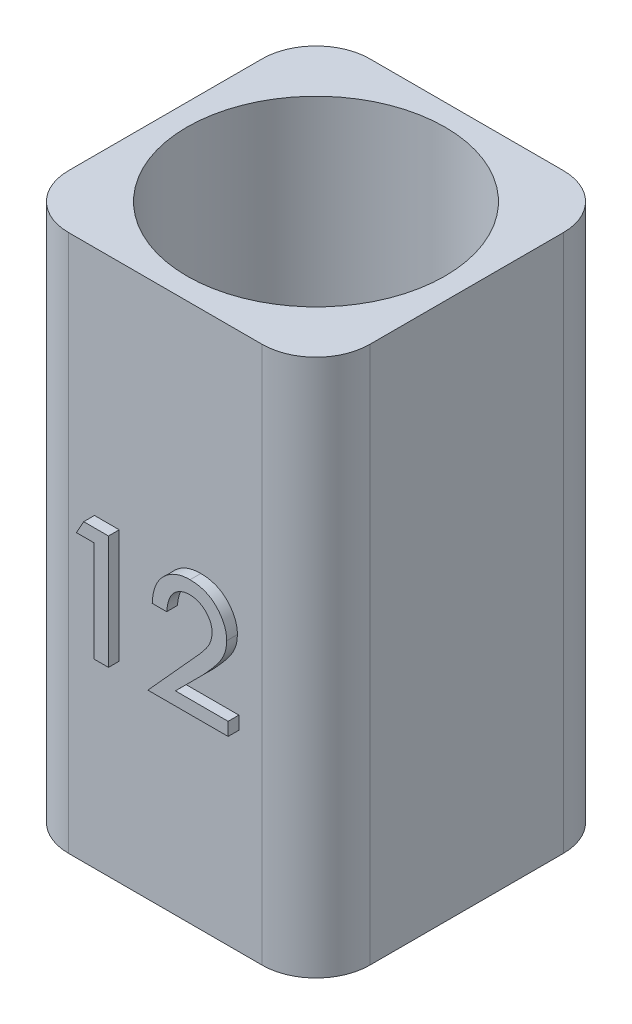
SolidWorks part; units mm, degrees
ref_plane "Ebene vorne" through (0, 0, 0) normal (0, 0, 1) x (1, 0, 0)
ref_plane "Ebene oben" through (0, 0, 0) normal (0, 1, 0) x (1, 0, 0)
ref_plane "Ebene rechts" through (0, 0, 0) normal (1, 0, 0) x (0, 0, -1)
sketch "Sketch1" plane through (0, 0, 0) normal (0, 1, 0) x (1, 0, 0)
  line L1 (7, -7) -> (-7, -7)
  line L2 (7, -7) -> (7, 7)
  line L3 (7, 7) -> (-7, 7)
  line L4 (-7, -7) -> (-7, 7)
  line L5 (7, -7) -> (-7, 7) construction
  line L6 (7, 7) -> (-7, -7) construction
  point P0 (0, 0)
  dimension "D1" = 14
  dimension "D2" = 14
extrude "Boss-Extrude1" add sketch "Sketch1" along normal blind 25
sketch "Sketch2" plane through (0, 25, 0) normal (0, 1, 0) x (1, 0, 0)
  circle A0 centre (0, 0) radius 6
  dimension "D1" = 12
extrude "Cut-Extrude1" cut sketch "Sketch2" against normal offset from surface (24 mm away) 1 up to face at (0, 0, 0)
sketch "Sketch3" plane through (0, 0, 7) normal (0, 0, 1) x (1, 0, 0)
  text T0 "<b>12</b>" font "Century Gothic" height in points 20
extrude "Boss-Extrude3" add sketch "Sketch3" along normal blind 0.5
fillet "Fillet1" radius 2.5 1 edges at (-7, 12.5, 7)
fillet "Fillet2" radius 2.5 1 edges at (7, 12.5, 7)
fillet "Fillet3" radius 2.5 1 edges at (7, 12.5, -7)
fillet "Fillet4" radius 2.5 1 edges at (-7, 12.5, -7)
